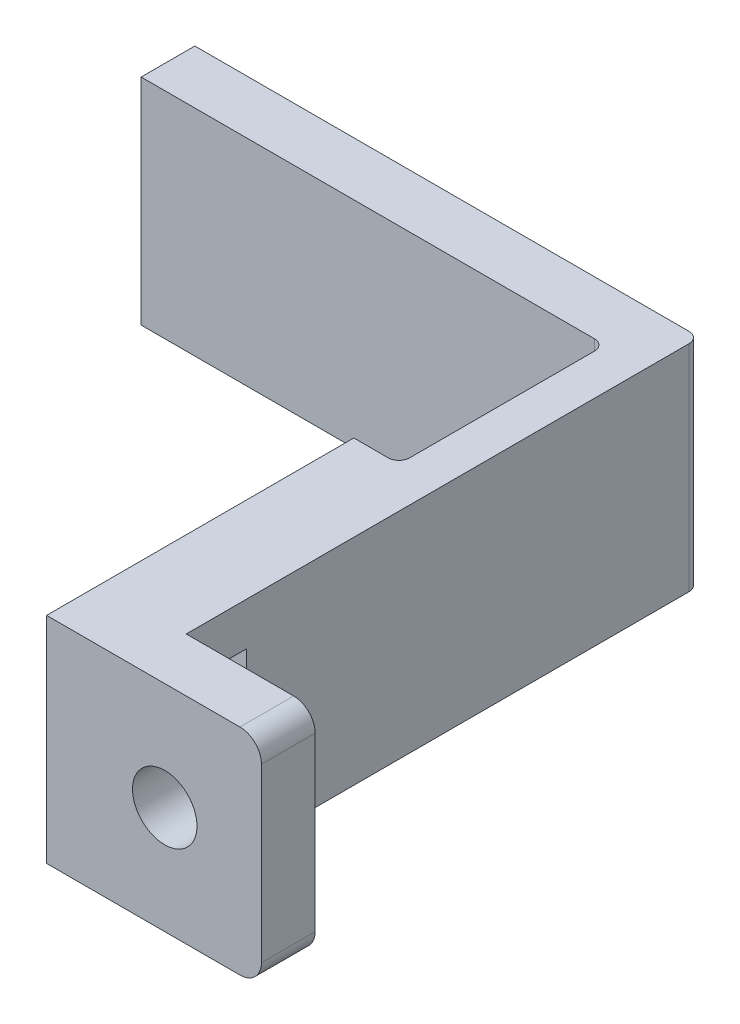
SolidWorks part; units mm, degrees
ref_plane "前视基准面" through (0, 0, 0) normal (0, 0, 1) x (1, 0, 0)
ref_plane "上视基准面" through (0, 0, 0) normal (0, 1, 0) x (1, 0, 0)
ref_plane "右视基准面" through (0, 0, 0) normal (1, 0, 0) x (0, 0, -1)
other "Configuration Table"
sketch "草图1" plane through (0, 0, 0) normal (0, 1, 0) x (1, 0, 0)
  line L0 (0, 0) -> (10, 0)
  line L1 (10, 0) -> (10, 2.5)
  line L2 (10, 2.5) -> (4, 2.5)
  line L3 (4, 2.5) -> (4, 26.4)
  line L4 (4, 26.4) -> (-19.5, 26.4)
  line L5 (-19.5, 26.4) -> (-19.5, 23.9)
  line L6 (-19.5, 23.9) -> (2.1, 23.9)
  line L7 (2.1, 23.9) -> (2.1, 14.3)
  line L8 (2.1, 14.3) -> (0, 14.3)
  line L9 (0, 14.3) -> (0, 0)
  dimension "D1" = 14.3
  dimension "D2" = 9.6
  dimension "D3" = 2.5
  dimension "D4" = 4
  dimension "D5" = 2.1
  dimension "D6" = 23.5
  dimension "D7" = 2.5
  dimension "D8" = 10
extrude "凸台-拉伸1" add sketch "草图1" along normal blind 10
sketch "草图2" plane through (0, 0, -2.5) normal (0, 0, -1) x (-1, 0, 0)
  line L0 (-10, 5) -> (-4, 5) construction
  line L1 (-10, 10) -> (-10, 0) construction
  line L2 (-4, 10) -> (-4, 0) construction
  circle A0 centre (-5.5, 5) radius 1.5
  dimension "D2" = 3
  dimension "D1" = 1.5
extrude "切除-拉伸1" cut sketch "草图2" against normal blind 10
fillet "圆角1" radius 0.5 2 edges at (2.1, 5, -23.9) (4, 5, -26.4)
fillet "圆角2" radius 0.5 1 edges at (2.1, 5, -14.3)
fillet "圆角3" radius 1 2 edges at (10, 10, -1.25) (10, 0, -1.25)
sketch "草图3" plane through (4, 0, 0) normal (1, 0, 0) x (0, 0, -1)
  line L0 (2.5, 9) -> (2.5, 1) construction
  line L1 (2.5, 8) -> (5.3, 8)
  line L2 (2.5, 8) -> (2.5, 2)
  line L3 (2.5, 2) -> (5.3, 2)
  line L4 (5.3, 8) -> (5.3, 2)
  line L5 (0, 5) -> (26.4, 5) construction
  line L6 (0, 9) -> (0, 1) construction
  line L7 (26.4, 10) -> (26.4, 0) construction
  dimension "D1" = 6
  dimension "D2" = 2.8
extrude "切除-拉伸2" cut sketch "草图3" against normal blind 2
